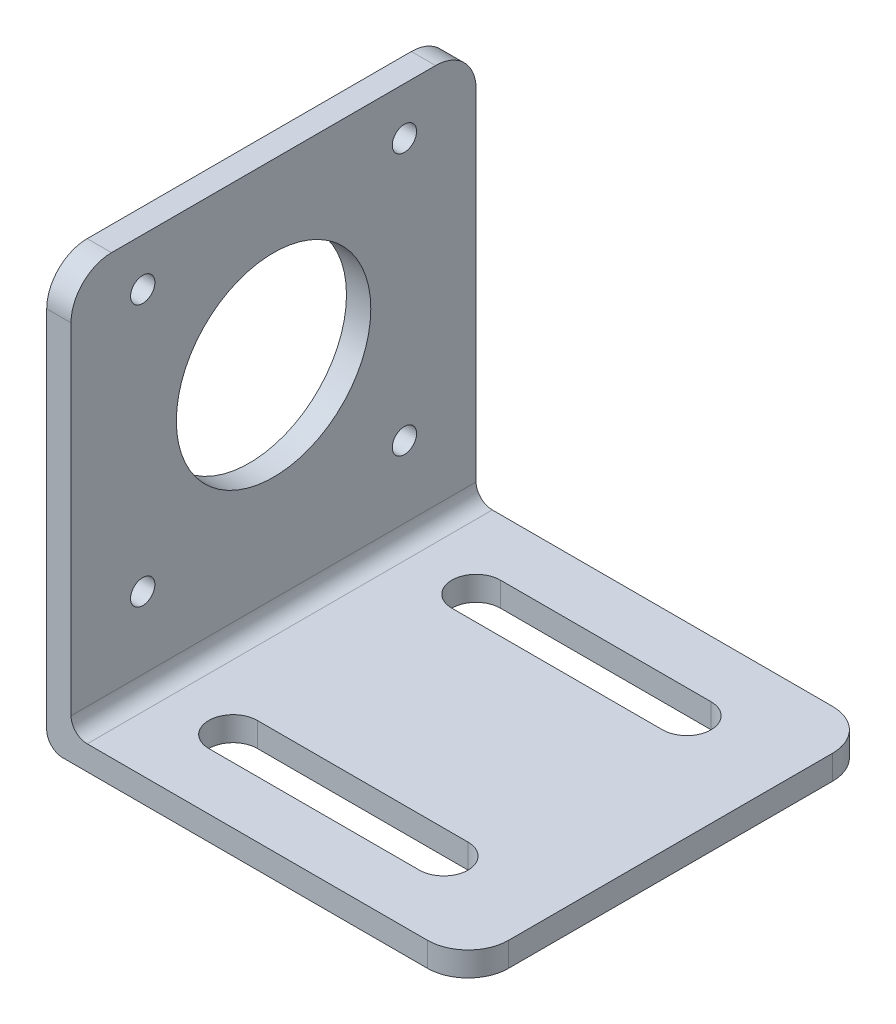
SolidWorks part; units mm, degrees
ref_plane "Front Plane" through (0, 0, 0) normal (0, 0, 1) x (1, 0, 0)
ref_plane "Top Plane" through (0, 0, 0) normal (0, 1, 0) x (1, 0, 0)
ref_plane "Right Plane" through (0, 0, 0) normal (1, 0, 0) x (0, 0, -1)
sketch "Sketch1" plane through (0, 0, 0) normal (0, 0, 1) x (1, 0, 0)
  line L0 (0, 0) -> (52, 0)
  line L1 (0, 0) -> (0, 52)
  line L2 (52, 0) -> (52, 3)
  line L3 (52, 3) -> (3, 3)
  line L4 (3, 3) -> (3, 52)
  line L5 (3, 52) -> (0, 52)
  dimension "D1" = 52
  dimension "D2" = 52
  dimension "D3" = 3
  dimension "D4" = 49
extrude "Boss-Extrude1" add sketch "Sketch1" along normal blind 50
fillet "Fillet1" radius 2 1 edges at (0, 0, 25)
fillet "Fillet2" radius 5 1 edges at (1.5, 52, 50)
fillet "Fillet3" radius 5 1 edges at (52, 1.5, 50)
fillet "Fillet4" radius 5 1 edges at (52, 1.5, 0)
fillet "Fillet5" radius 5 1 edges at (1.5, 52, 0)
fillet "Fillet6" radius 2 1 edges at (3, 3, 25)
sketch "Sketch2" plane through (0, 3, 0) normal (0, 1, 0) x (1, 0, 0)
  line L0 (39, -40) -> (13, -40) construction
  line L1 (39, -43) -> (13, -43)
  line L2 (39, -37) -> (13, -37)
  line L3 (0, -45) -> (0, -5) construction
  line L4 (52, -45) -> (52, -5) construction
  line L5 (47, -50) -> (5, -50) construction
  line L6 (13, -10) -> (39, -10) construction
  line L7 (13, -7) -> (39, -7)
  line L8 (13, -13) -> (39, -13)
  line L9 (47, 0) -> (5, 0) construction
  arc A0 (39, -43) -> (39, -37) centre (39, -40) ccw
  arc A1 (13, -37) -> (13, -43) centre (13, -40) ccw
  arc A2 (13, -7) -> (13, -13) centre (13, -10) ccw
  arc A3 (39, -13) -> (39, -7) centre (39, -10) ccw
  point P2 (26, -40)
  point P15 (26, -10)
  dimension "D4" = 3
  dimension "D6" = 3
  dimension "D1" = 13
  dimension "D2" = 13
  dimension "D3" = 10
  dimension "D5" = 10
extrude "Cut-Extrude1" cut sketch "Sketch2" against normal blind 50
sketch "Sketch3" plane through (0, 0, 0) normal (-1, 0, 0) x (0, 0, 1)
  line L0 (45, 52) -> (5, 52) construction
  circle A0 centre (25, 30) radius 12
  dimension "D2" = 24
  dimension "D1" = 22
extrude "Cut-Extrude2" cut sketch "Sketch3" against normal blind 50
sketch "Sketch4" plane through (3, 0, 0) normal (1, 0, 0) x (0, 0, -1)
  circle A0 centre (-8.85, 46.15) radius 1.5
  circle A1 centre (-41.15, 46.15) radius 1.5
  circle A2 centre (-8.85, 13.85) radius 1.5
  circle A3 centre (-41.15, 13.85) radius 1.5
extrude "Cut-Extrude3" cut sketch "Sketch4" against normal blind 10
